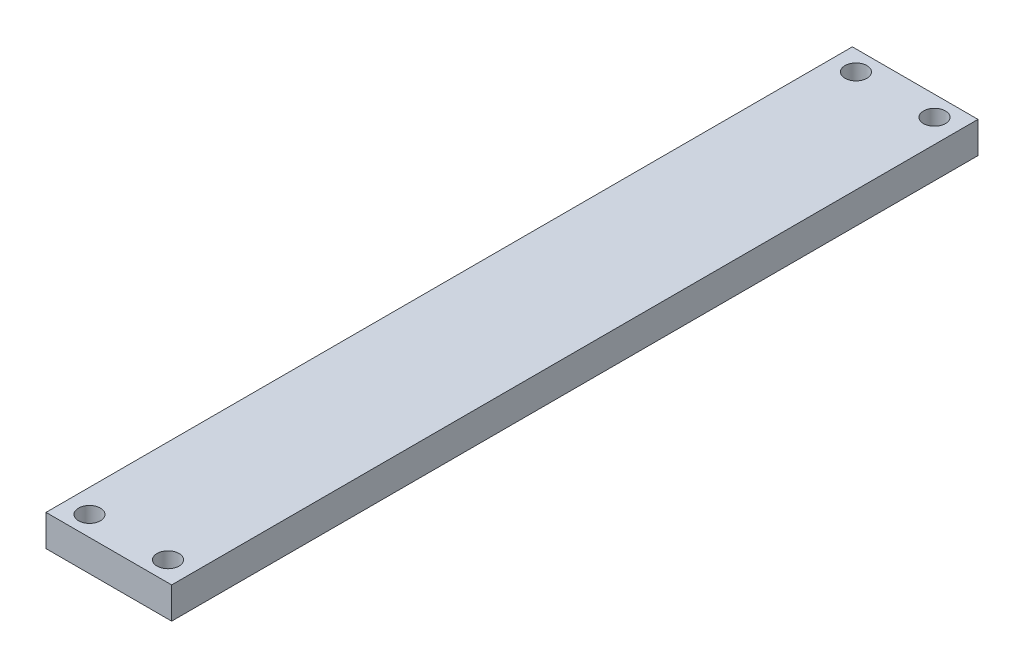
SolidWorks part; units mm, degrees
material "6061-T6 (SS)"
ref_plane "Front Plane" through (0, 0, 0) normal (0, 0, 1) x (1, 0, 0)
ref_plane "Top Plane" through (0, 0, 0) normal (0, 1, 0) x (1, 0, 0)
ref_plane "Right Plane" through (0, 0, 0) normal (1, 0, 0) x (0, 0, -1)
sketch "Sketch1" plane through (0, 0, 0) normal (0, 0, 1) x (1, 0, 0)
  line L1 (-10, -2.5) -> (10, -2.5)
  line L2 (-10, -2.5) -> (-10, 2.5)
  line L3 (-10, 2.5) -> (10, 2.5)
  line L4 (10, -2.5) -> (10, 2.5)
  line L5 (0, 2.5) -> (0, -2.5) construction
  line L6 (-10, 0) -> (10, 0) construction
  point P0 (0, 0)
  dimension "D1" = 20
  dimension "D2" = 5
extrude "Boss-Extrude1" add sketch "Sketch1" along normal mid plane 128.35
sketch "Sketch2" plane through (0, 2.5, 0) normal (0, 1, 0) x (1, 0, 0)
  line L0 (0, 64.175) -> (0, -64.175) construction
  line L1 (10, 64.175) -> (-10, 64.175) construction
  line L2 (10, -64.175) -> (-10, -64.175) construction
  line L3 (10, 0) -> (-10, 0) construction
  line L4 (10, -64.175) -> (10, 64.175) construction
  line L5 (-10, -64.175) -> (-10, 64.175) construction
  circle A0 centre (-6.25, -61) radius 1.75
  circle A1 centre (6.25, -61) radius 1.75
  circle A2 centre (6.25, 61) radius 1.75
  circle A3 centre (-6.25, 61) radius 1.75
  dimension "D3" = 3.5
  dimension "D1" = 12.5
  dimension "D2" = 12.5
  dimension "D4" = 3.175
extrude "Cut-Extrude1" cut sketch "Sketch2" against normal through all
